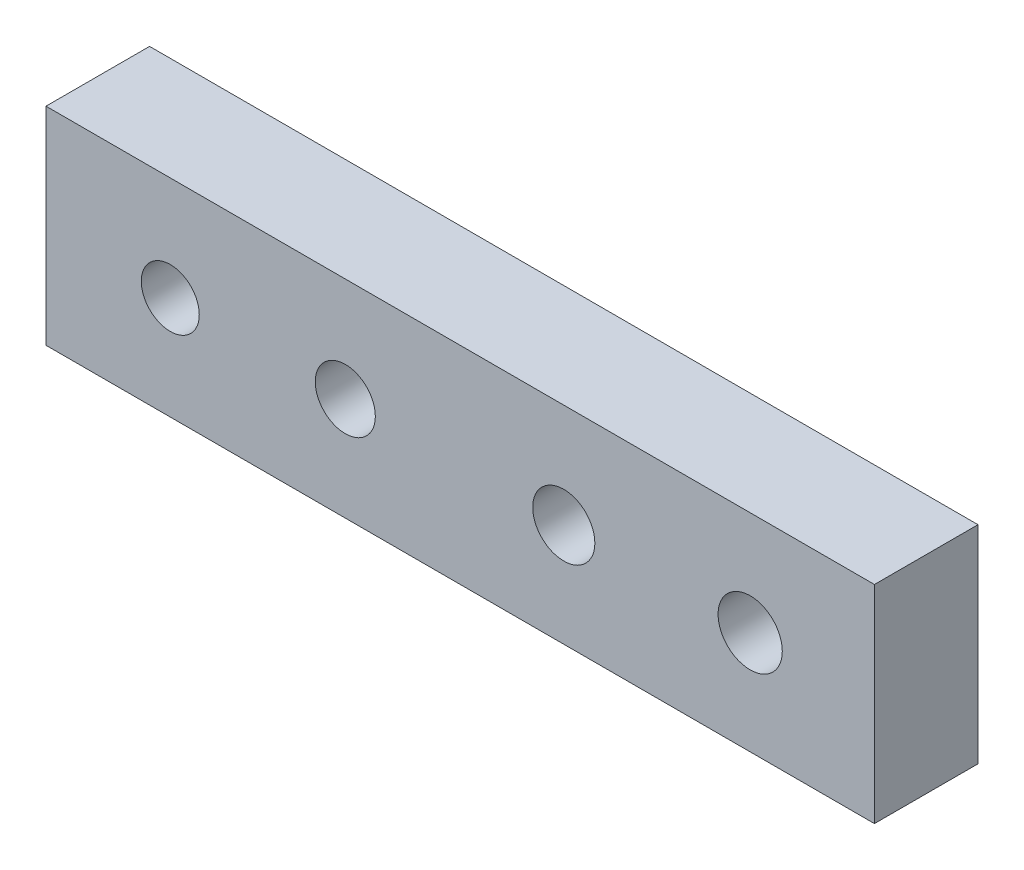
SolidWorks part; units mm, degrees
ref_plane "Front Plane" through (0, 0, 0) normal (0, 0, 1) x (1, 0, 0)
ref_plane "Top Plane" through (0, 0, 0) normal (0, 1, 0) x (1, 0, 0)
ref_plane "Right Plane" through (0, 0, 0) normal (1, 0, 0) x (0, 0, -1)
sketch "Sketch2" plane through (0, 0, 0) normal (0, 0, 1) x (1, 0, 0)
  line L1 (0, 0) -> (40, 0)
  line L2 (0, 0) -> (0, -10)
  line L3 (0, -10) -> (40, -10)
  line L4 (40, 0) -> (40, -10)
  dimension "D1" = 40
  dimension "D2" = 10
extrude "Boss-Extrude1" add sketch "Sketch2" along normal blind 5
sketch "Sketch3" plane through (0, 0, 5) normal (0, 0, 1) x (1, 0, 0)
  line L0 (0, 0) -> (0, -10) construction
  line L1 (40, -10) -> (40, 0) construction
  circle A0 centre (6, -5.0203) radius 1.4
  circle A1 centre (14.4512, -5.0203) radius 1.45
  circle A2 centre (25, -5.0203) radius 1.5
  circle A3 centre (34, -5.0203) radius 1.55
  dimension "D1" = 2.8
  dimension "D2" = 2.9
  dimension "D3" = 3
  dimension "D4" = 3.1
  dimension "D5" = 9
  dimension "D6" = 6
  dimension "D7" = 6
extrude "Cut-Extrude1" cut sketch "Sketch3" against normal blind 5
